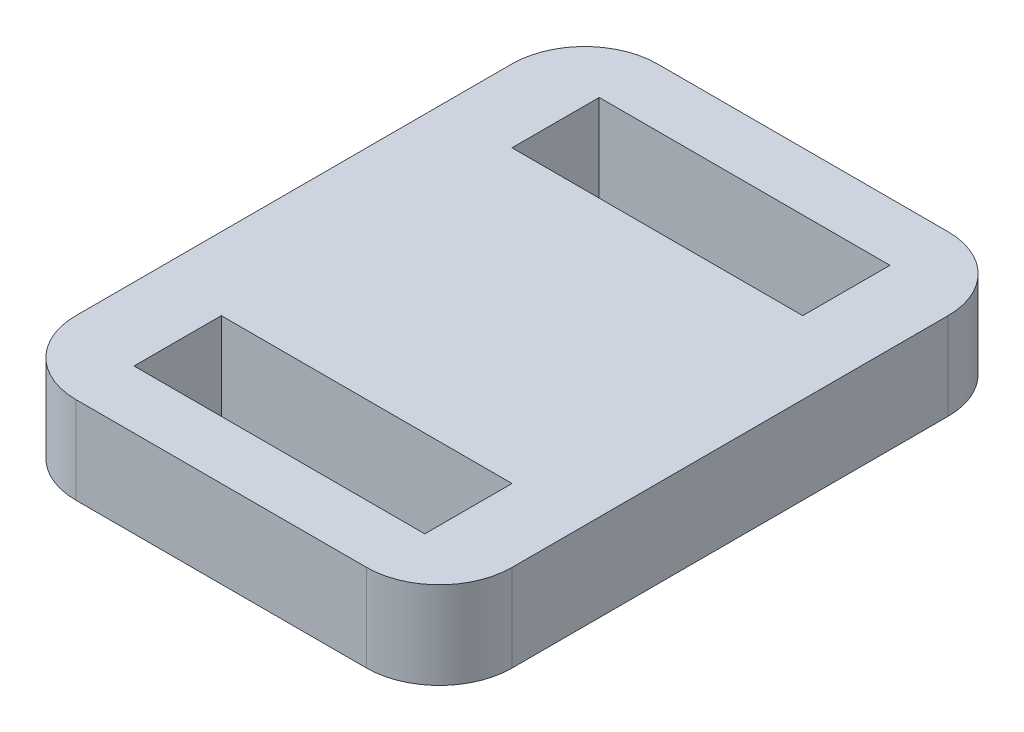
SolidWorks part; units mm, degrees
ref_plane "Front Plane" through (0, 0, 0) normal (0, 0, 1) x (1, 0, 0)
ref_plane "Top Plane" through (0, 0, 0) normal (0, 1, 0) x (1, 0, 0)
ref_plane "Right Plane" through (0, 0, 0) normal (1, 0, 0) x (0, 0, -1)
other "Configuration Table"
sketch "Sketch1" plane through (0, 0, 0) normal (0, 1, 0) x (1, 0, 0)
  line L0 (-10, 29) -> (10, 29)
  line L1 (-10, 3) -> (10, 3)
  line L2 (-10, 3) -> (-10, -3)
  line L3 (-10, -3) -> (10, -3)
  line L4 (10, 3) -> (10, -3)
  line L5 (-10, 3) -> (10, -3) construction
  line L6 (-10, -3) -> (10, 3) construction
  line L7 (-10, 33) -> (10, 33)
  line L8 (-15, 28) -> (-15, -2)
  line L9 (-10, -7) -> (10, -7)
  line L10 (15, 28) -> (15, -2)
  line L11 (-15, 33) -> (15, -7) construction
  line L12 (-15, -7) -> (15, 33) construction
  line L13 (-10, 29) -> (-10, 23)
  line L14 (-10, 23) -> (10, 23)
  line L15 (10, 29) -> (10, 23)
  line L16 (-10, 29) -> (10, 23) construction
  line L17 (-10, 23) -> (10, 29) construction
  arc A0 (15, -2) -> (10, -7) centre (10, -2) cw
  arc A1 (-10, -7) -> (-15, -2) centre (-10, -2) cw
  arc A2 (15, 28) -> (10, 33) centre (10, 28) ccw
  arc A3 (-10, 33) -> (-15, 28) centre (-10, 28) ccw
  point P0 (0, 0)
  point P6 (0, 13)
  point P11 (0, 26)
  dimension "D10" = 5
  dimension "D1" = 20
  dimension "D2" = 6
  dimension "D3" = 20
  dimension "D4" = 6
  dimension "D5" = 20
  dimension "D6" = 40
  dimension "D7" = 30
  dimension "D8" = 15
  dimension "D9" = 4
extrude "Boss-Extrude1" add sketch "Sketch1" along normal blind 6
